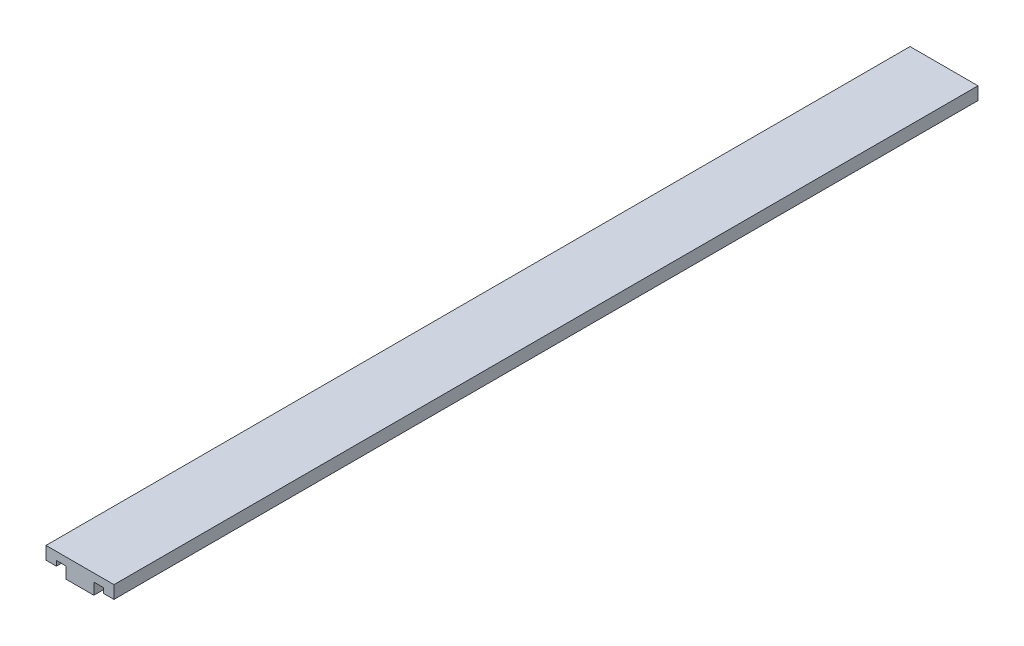
SolidWorks part; units mm, degrees
material "Aço inoxidável forjado"
ref_plane "Plano frontal" through (0, 0, 0) normal (0, 0, 1) x (1, 0, 0)
ref_plane "Plano superior" through (0, 0, 0) normal (0, 1, 0) x (1, 0, 0)
ref_plane "Plano direito" through (0, 0, 0) normal (1, 0, 0) x (0, 0, -1)
sketch "Esboço1" plane through (0, 0, 0) normal (0, 0, 1) x (1, 0, 0)
  line L0 (-0.6001, -33.5) -> (-0.6001, -31.5124)
  line L1 (10, -33.5) -> (-43.05, -33.5) construction
  line L2 (1.0999, -31.5124) -> (-0.6001, -31.5124)
  line L3 (1.0999, -32.3804) -> (1.0999, -31.5124)
  line L4 (1.0999, -32.3804) -> (2.8999, -32.3804)
  line L5 (2.8999, -32.3804) -> (2.8999, -30.1504)
  line L6 (2.8999, -30.1504) -> (-8.9001, -30.1504)
  line L7 (-8.9001, -30.1504) -> (-8.9001, -32.3804)
  line L8 (-8.9001, -32.3804) -> (-7.1001, -32.3804)
  line L9 (-7.1001, -32.3804) -> (-7.1001, -31.5104)
  line L10 (-7.1001, -31.5104) -> (-5.4001, -31.5104)
  line L11 (-5.4001, -31.5104) -> (-5.4001, -33.5)
  line L12 (-5.4001, -33.5) -> (-0.6001, -33.5)
  point P14 (-7.1001, -31.9454)
  dimension "D1" = 2.23
  dimension "D2" = 2.23
  dimension "D3" = 1.362
  dimension "D4" = 1.36
  dimension "D5" = 1.8
  dimension "D6" = 1.7
  dimension "D7" = 1.8
  dimension "D8" = 1.7
  dimension "D9" = 4.8
  dimension "D10" = 3.3496
extrude "Ressalto-extrusão1" add sketch "Esboço1" against normal blind 150
